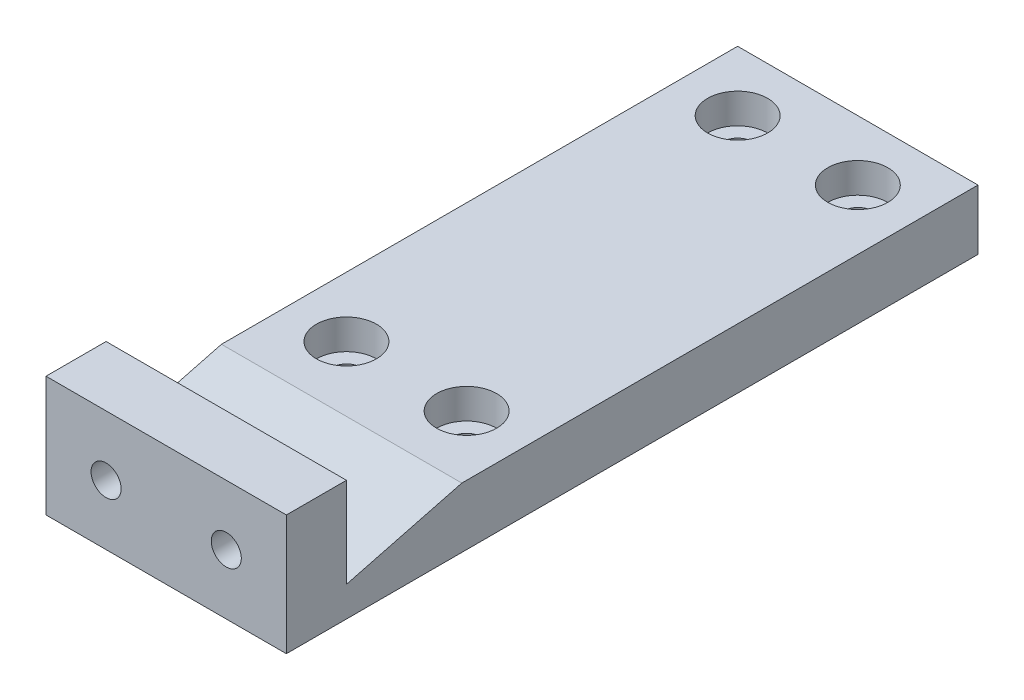
SolidWorks part; units mm, degrees
ref_plane "Front Plane" through (0, 0, 0) normal (0, 0, 1) x (1, 0, 0)
ref_plane "Top Plane" through (0, 0, 0) normal (0, 1, 0) x (1, 0, 0)
ref_plane "Right Plane" through (0, 0, 0) normal (1, 0, 0) x (0, 0, -1)
other "Configuration Table"
sketch "Sketch1" plane through (0, 0, 0) normal (0, 1, 0) x (1, 0, 0)
  line L1 (20, -57.55) -> (-20, -57.55)
  line L2 (20, -57.55) -> (20, 57.55)
  line L3 (20, 57.55) -> (-20, 57.55)
  line L4 (-20, -57.55) -> (-20, 57.55)
  line L5 (20, -57.55) -> (-20, 57.55) construction
  line L6 (20, 57.55) -> (-20, -57.55) construction
  point P0 (0, 0)
  dimension "D1" = 115.1
  dimension "D2" = 40
extrude "Boss-Extrude1" add sketch "Sketch1" along normal blind 10
sketch "Sketch2" plane through (0, 10, 0) normal (0, 1, 0) x (1, 0, 0)
  line L0 (-20, 57.55) -> (-20, -57.55) construction
  line L1 (-20, -47.55) -> (20, -47.55)
  line L2 (-20, -47.55) -> (-20, -57.55)
  line L3 (-20, -57.55) -> (20, -57.55)
  line L4 (20, -47.55) -> (20, -57.55)
  dimension "D1" = 10
extrude "Boss-Extrude2" add sketch "Sketch2" along normal blind 10
sketch "Sketch3" plane through (0, 10, 0) normal (0, 1, 0) x (1, 0, 0)
  line L0 (0, -47.55) -> (0, 57.55) construction
  line L1 (20, -47.55) -> (-20, -47.55) construction
  line L2 (20, 57.55) -> (-20, 57.55) construction
  line L3 (-20, 57.55) -> (-20, -47.55) construction
  line L4 (20, -47.55) -> (20, 57.55) construction
  circle A0 centre (-10, 47.55) radius 2.5
  circle A1 centre (10, 47.55) radius 2.5
  circle A2 centre (10, -17.55) radius 2.5
  circle A3 centre (-10, -17.55) radius 2.5
  dimension "D1" = 5
  dimension "D2" = 5
  dimension "D3" = 5
  dimension "D4" = 5
  dimension "D5" = 10
  dimension "D6" = 10
  dimension "D7" = 10
  dimension "D8" = 10
  dimension "D9" = 10
  dimension "D10" = 10
  dimension "D11" = 30
  dimension "D12" = 30
extrude "Cut-Extrude1" cut sketch "Sketch3" against normal through all both and the other way through all
sketch "Sketch4" plane through (0, 10, 0) normal (0, 1, 0) x (1, 0, 0)
  circle A0 centre (10, 47.55) radius 5
  circle A1 centre (-10, 47.55) radius 5
  circle A2 centre (10, -17.55) radius 5
  circle A3 centre (-10, -17.55) radius 5
extrude "Cut-Extrude2" cut sketch "Sketch4" against normal blind 5
sketch "Sketch5" plane through (-20, 0, 0) normal (-1, 0, 0) x (0, 0, 1)
  line L0 (28.35, 10) -> (47.55, 5)
  line L1 (-57.55, 10) -> (47.55, 10) construction
  line L2 (47.55, 5) -> (47.55, 10)
  line L3 (47.55, 10) -> (28.35, 10)
  line L4 (-57.55, 0) -> (57.55, 0) construction
  point P7 (0, 0)
  dimension "D1" = 5
extrude "Cut-Extrude3" cut sketch "Sketch5" against normal through all both and the other way through all
sketch "Sketch6" plane through (0, 0, 47.55) normal (0, 0, -1) x (-1, 0, 0)
  line L0 (0, 0) -> (0, 20) construction
  line L1 (-20, 20) -> (20, 20) construction
  line L2 (-20, 10) -> (20, 10) construction
  circle A0 centre (-10, 10) radius 2.5
  circle A1 centre (10, 10) radius 2.5
  dimension "D1" = 10
  dimension "D2" = 10
extrude "Cut-Extrude4" cut sketch "Sketch6" against normal through all
sketch "Sketch7" plane through (0, 0, 47.55) normal (0, 0, -1) x (-1, 0, 0)
  circle A0 centre (-10, 10) radius 5
  circle A1 centre (10, 10) radius 5
extrude "Cut-Extrude5" cut sketch "Sketch7" against normal blind 5
